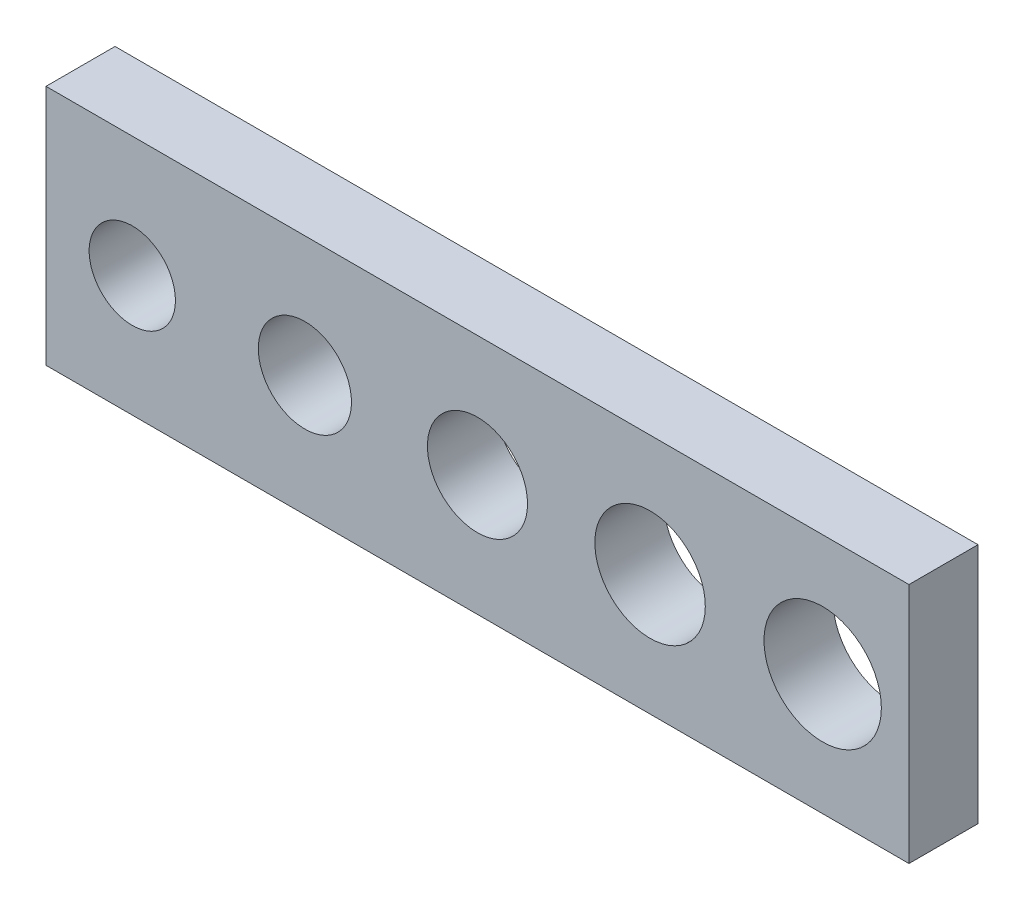
SolidWorks part; units mm, degrees
ref_plane "Front" through (0, 0, 0) normal (0, 0, 1) x (1, 0, 0)
ref_plane "Top" through (0, 0, 0) normal (0, 1, 0) x (1, 0, 0)
ref_plane "Right" through (0, 0, 0) normal (1, 0, 0) x (0, 0, -1)
sketch "Sketch1" plane through (0, 0, 0) normal (0, 0, 1) x (1, 0, 0)
  line L0 (0, 0) -> (63.5, 0)
  line L1 (0, 0) -> (0, 17.78)
  line L2 (63.5, 0) -> (63.5, 17.78)
  line L3 (0, 17.78) -> (63.5, 17.78)
  line L4 (0, 8.89) -> (63.5, 8.89) construction
  circle A0 centre (6.35, 8.89) radius 3.175
  circle A1 centre (19.05, 8.89) radius 3.429
  circle A2 centre (31.75, 8.89) radius 3.683
  circle A3 centre (44.45, 8.89) radius 4.064
  circle A4 centre (57.15, 8.89) radius 4.318
  dimension "D3" = 6.35
  dimension "D4" = 6.858
  dimension "D5" = 7.366
  dimension "D6" = 8.128
  dimension "D12" = 8.636
  dimension "D1" = 17.78
  dimension "D2" = 63.5
  dimension "D7" = 6.35
  dimension "D8" = 12.7
  dimension "D9" = 12.7
  dimension "D10" = 12.7
  dimension "D11" = 6.35
extrude "Boss-Extrude1" add sketch "Sketch1" along normal blind 5.08
